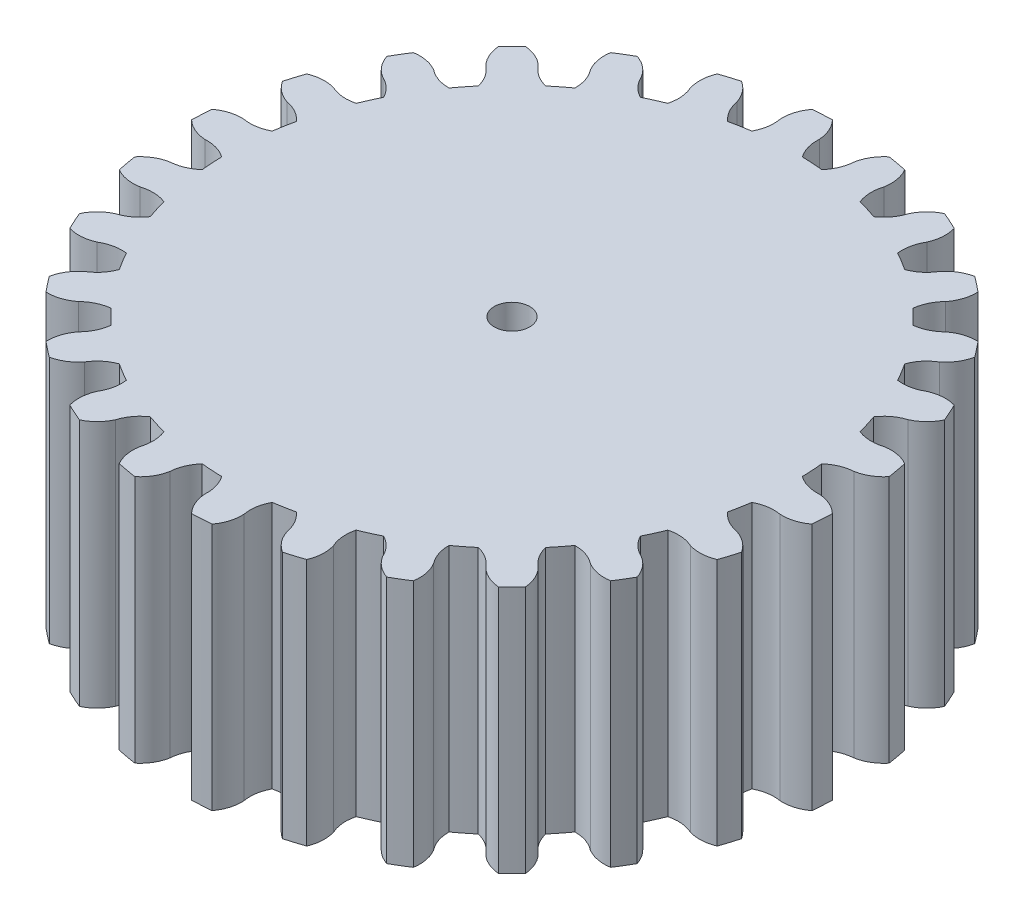
SolidWorks part; units mm, degrees
ref_plane "Alzado" through (0, 0, 0) normal (0, 0, 1) x (1, 0, 0)
ref_plane "Planta" through (0, 0, 0) normal (0, 1, 0) x (1, 0, 0)
ref_plane "Vista lateral" through (0, 0, 0) normal (1, 0, 0) x (0, 0, -1)
sketch "Croquis1" plane through (0, 0, 0) normal (0, 1, 0) x (1, 0, 0)
  circle A0 centre (0, 0) radius 18.6665
  circle A1 centre (0, 0) radius 1
  dimension "D1" = 37.3329
  dimension "D2" = 2
extrude "Saliente-Extruir1" add sketch "Croquis1" along normal blind 14
sketch "Croquis3" plane through (0, 14, 0) normal (0, 1, 0) x (1, 0, 0)
  line L0 (0, 17.333) -> (0, 0) construction
  arc A0 (2.8263, 18.4512) -> (-0.5803, 18.6574) centre (0, 0) ccw
  arc A4 (0, 17.333) -> (0.3822, 15.9949) centre (2.0905, 17.2064) ccw
  arc A5 (2.8263, 18.4512) -> (2.0905, 17.2064) centre (4.1505, 16.8287) ccw
  arc A6 (0, 17.333) -> (-0.5803, 18.6574) centre (-2.0905, 17.2064) ccw
  arc A7 (4.148, 16.8293) -> (3.9016, 18.2541) centre (2.088, 17.2067) ccw
  arc A8 (1.5498, 15.9242) -> (0.3822, 15.9949) centre (0, 0) ccw
  arc A9 (1.5498, 15.9242) -> (2.0905, 17.2064) centre (0, 17.333) ccw
  arc A10 (7.1598, 17.2387) -> (3.9016, 18.2541) centre (0, 0) ccw
  arc A11 (7.1598, 17.2387) -> (6.1475, 16.2061) centre (8.0573, 15.3464) ccw
  arc A12 (5.3156, 15.0906) -> (6.1475, 16.2061) centre (4.148, 16.8293) ccw
  arc A13 (5.3156, 15.0906) -> (4.1989, 15.4386) centre (0, 0) ccw
  arc A14 (4.148, 16.8293) -> (4.1989, 15.4386) centre (6.1475, 16.2061) ccw
  arc A15 (8.055, 15.3476) -> (8.1567, 16.79) centre (6.1452, 16.207) ccw
  arc A16 (11.0773, 15.0243) -> (8.1567, 16.79) centre (0, 0) ccw
  arc A17 (11.0773, 15.0243) -> (9.8473, 14.264) centre (11.4958, 12.9722) ccw
  arc A18 (8.7726, 13.38) -> (9.8473, 14.264) centre (8.055, 15.3476) ccw
  arc A19 (8.7726, 13.38) -> (7.7716, 13.9852) centre (0, 0) ccw
  arc A20 (8.055, 15.3476) -> (7.7716, 13.9852) centre (9.8473, 14.264) ccw
  arc A21 (11.4939, 12.9739) -> (11.9378, 14.3501) centre (9.8452, 14.2655) ccw
  arc A22 (14.351, 11.9368) -> (11.9378, 14.3501) centre (0, 0) ccw
  arc A23 (14.351, 11.9368) -> (12.9747, 11.4929) centre (14.2662, 9.8441) ccw
  arc A24 (11.7197, 10.8918) -> (12.9747, 11.4929) centre (11.4939, 12.9739) ccw
  arc A25 (11.7197, 10.8918) -> (10.8926, 11.7189) centre (0, 0) ccw
  arc A26 (11.4939, 12.9739) -> (10.8926, 11.7189) centre (12.9747, 11.4929) ccw
  arc A27 (14.2647, 9.8462) -> (15.0251, 11.0762) centre (12.9731, 11.4948) ccw
  arc A28 (16.7906, 8.1555) -> (15.0251, 11.0762) centre (0, 0) ccw
  arc A29 (16.7906, 8.1555) -> (15.3482, 8.0539) centre (16.2075, 6.144) ccw
  arc A30 (13.9857, 7.7706) -> (15.3482, 8.0539) centre (14.2647, 9.8462) ccw
  arc A31 (13.9857, 7.7706) -> (13.3806, 8.7716) centre (0, 0) ccw
  arc A32 (14.2647, 9.8462) -> (13.3806, 8.7716) centre (15.3482, 8.0539) ccw
  arc A33 (16.2066, 6.1463) -> (17.2392, 7.1586) centre (15.347, 8.0562) ccw
  arc A34 (18.2544, 3.9003) -> (17.2392, 7.1586) centre (0, 0) ccw
  arc A35 (18.2544, 3.9003) -> (16.8296, 4.1468) centre (17.2069, 2.0867) ccw
  arc A36 (15.439, 4.1978) -> (16.8296, 4.1468) centre (16.2066, 6.1463) ccw
  arc A37 (15.439, 4.1978) -> (15.091, 5.3145) centre (0, 0) ccw
  arc A38 (16.2066, 6.1463) -> (15.091, 5.3145) centre (16.8296, 4.1468) ccw
  arc A39 (17.2066, 2.0893) -> (18.4515, 2.8249) centre (16.829, 4.1493) ccw
  arc A40 (18.6574, -0.5816) -> (18.4515, 2.8249) centre (0, 0) ccw
  arc A41 (18.6574, -0.5816) -> (17.3329, -0.0013) centre (17.2063, -2.0918) ccw
  arc A42 (15.9949, 0.381) -> (17.3329, -0.0013) centre (17.2066, 2.0893) ccw
  arc A43 (15.9949, 0.381) -> (15.9243, 1.5486) centre (0, 0) ccw
  arc A44 (17.2066, 2.0893) -> (15.9243, 1.5486) centre (17.3329, -0.0013) ccw
  arc A45 (17.2066, -2.0893) -> (18.5913, -1.6729) centre (17.3329, 0.0013) ccw
  arc A46 (17.976, -5.0297) -> (18.5913, -1.6729) centre (0, 0) ccw
  arc A47 (17.976, -5.0297) -> (16.829, -4.1493) centre (16.2057, -6.1487) ccw
  arc A48 (15.6213, -3.4579) -> (16.829, -4.1493) centre (17.2066, -2.0893) ccw
  arc A49 (15.6213, -3.4579) -> (15.8322, -2.3074) centre (0, 0) ccw
  arc A50 (17.2066, -2.0893) -> (15.8322, -2.3074) centre (16.829, -4.1493) ccw
  arc A51 (16.2066, -6.1463) -> (17.6508, -6.0735) centre (16.8296, -4.1468) ccw
  arc A52 (16.25, -9.1855) -> (17.6508, -6.0735) centre (0, 0) ccw
  arc A53 (16.25, -9.1855) -> (15.347, -8.0562) centre (14.2633, -9.8483) ccw
  arc A54 (14.3398, -7.0959) -> (15.347, -8.0562) centre (16.2066, -6.1463) ccw
  arc A55 (14.3398, -7.0959) -> (14.82, -6.0292) centre (0, 0) ccw
  arc A56 (16.2066, -6.1463) -> (14.82, -6.0292) centre (15.347, -8.0562) ccw
  arc A57 (14.2647, -9.8462) -> (15.6844, -10.1211) centre (15.3482, -8.0539) ccw
  arc A58 (13.5796, -12.8075) -> (15.6844, -10.1211) centre (0, 0) ccw
  arc A59 (13.5796, -12.8075) -> (12.9731, -11.4948) centre (11.492, -12.9756) ccw
  arc A60 (12.225, -10.3214) -> (12.9731, -11.4948) centre (14.2647, -9.8462) ccw
  arc A61 (12.225, -10.3214) -> (12.9464, -9.4006) centre (0, 0) ccw
  arc A62 (14.2647, -9.8462) -> (12.9464, -9.4006) centre (12.9731, -11.4948) ccw
  arc A63 (11.4939, -12.9739) -> (12.8065, -13.5805) centre (12.9747, -11.4929) ccw
  arc A64 (10.1199, -15.6851) -> (12.8065, -13.5805) centre (0, 0) ccw
  arc A65 (10.1199, -15.6851) -> (9.8452, -14.2655) centre (8.0528, -15.3488) ccw
  arc A66 (9.3997, -12.9471) -> (9.8452, -14.2655) centre (11.4939, -12.9739) ccw
  arc A67 (9.3997, -12.9471) -> (10.3205, -12.2258) centre (0, 0) ccw
  arc A68 (11.4939, -12.9739) -> (10.3205, -12.2258) centre (9.8452, -14.2655) ccw
  arc A69 (8.055, -15.3476) -> (9.1843, -16.2507) centre (9.8473, -14.264) ccw
  arc A70 (6.0722, -17.6512) -> (9.1843, -16.2507) centre (0, 0) ccw
  arc A71 (6.0722, -17.6512) -> (6.1452, -16.207) centre (4.1456, -16.8299) ccw
  arc A72 (6.0281, -14.8204) -> (6.1452, -16.207) centre (8.055, -15.3476) ccw
  arc A73 (6.0281, -14.8204) -> (7.0948, -14.3404) centre (0, 0) ccw
  arc A74 (8.055, -15.3476) -> (7.0948, -14.3404) centre (6.1452, -16.207) ccw
  arc A75 (4.148, -16.8293) -> (5.0284, -17.9764) centre (6.1475, -16.2061) ccw
  arc A76 (1.6715, -18.5915) -> (5.0284, -17.9764) centre (0, 0) ccw
  arc A77 (1.6715, -18.5915) -> (2.088, -17.2067) centre (-0.0026, -17.3329) ccw
  arc A78 (2.3062, -15.8324) -> (2.088, -17.2067) centre (4.148, -16.8293) ccw
  arc A79 (2.3062, -15.8324) -> (3.4568, -15.6216) centre (0, 0) ccw
  arc A80 (4.148, -16.8293) -> (3.4568, -15.6216) centre (2.088, -17.2067) ccw
  arc A81 (0, -17.333) -> (0.5803, -18.6574) centre (2.0905, -17.2064) ccw
  arc A82 (-2.8263, -18.4512) -> (0.5803, -18.6574) centre (0, 0) ccw
  arc A83 (-2.8263, -18.4512) -> (-2.0905, -17.2064) centre (-4.1505, -16.8287) ccw
  arc A84 (-1.5498, -15.9242) -> (-2.0905, -17.2064) centre (0, -17.333) ccw
  arc A85 (-1.5498, -15.9242) -> (-0.3822, -15.9949) centre (0, 0) ccw
  arc A86 (0, -17.333) -> (-0.3822, -15.9949) centre (-2.0905, -17.2064) ccw
  arc A87 (-4.148, -16.8293) -> (-3.9016, -18.2541) centre (-2.088, -17.2067) ccw
  arc A88 (-7.1598, -17.2387) -> (-3.9016, -18.2541) centre (0, 0) ccw
  arc A89 (-7.1598, -17.2387) -> (-6.1475, -16.2061) centre (-8.0573, -15.3464) ccw
  arc A90 (-5.3156, -15.0906) -> (-6.1475, -16.2061) centre (-4.148, -16.8293) ccw
  arc A91 (-5.3156, -15.0906) -> (-4.1989, -15.4386) centre (0, 0) ccw
  arc A92 (-4.148, -16.8293) -> (-4.1989, -15.4386) centre (-6.1475, -16.2061) ccw
  arc A93 (-8.055, -15.3476) -> (-8.1567, -16.79) centre (-6.1452, -16.207) ccw
  arc A94 (-11.0773, -15.0243) -> (-8.1567, -16.79) centre (0, 0) ccw
  arc A95 (-11.0773, -15.0243) -> (-9.8473, -14.264) centre (-11.4958, -12.9722) ccw
  arc A96 (-8.7726, -13.38) -> (-9.8473, -14.264) centre (-8.055, -15.3476) ccw
  arc A97 (-8.7726, -13.38) -> (-7.7716, -13.9852) centre (0, 0) ccw
  arc A98 (-8.055, -15.3476) -> (-7.7716, -13.9852) centre (-9.8473, -14.264) ccw
  arc A99 (-11.4939, -12.9739) -> (-11.9378, -14.3501) centre (-9.8452, -14.2655) ccw
  arc A100 (-14.351, -11.9368) -> (-11.9378, -14.3501) centre (0, 0) ccw
  arc A101 (-14.351, -11.9368) -> (-12.9747, -11.4929) centre (-14.2662, -9.8441) ccw
  arc A102 (-11.7197, -10.8918) -> (-12.9747, -11.4929) centre (-11.4939, -12.9739) ccw
  arc A103 (-11.7197, -10.8918) -> (-10.8926, -11.7189) centre (0, 0) ccw
  arc A104 (-11.4939, -12.9739) -> (-10.8926, -11.7189) centre (-12.9747, -11.4929) ccw
  arc A105 (-14.2647, -9.8462) -> (-15.0251, -11.0762) centre (-12.9731, -11.4948) ccw
  arc A106 (-16.7906, -8.1555) -> (-15.0251, -11.0762) centre (0, 0) ccw
  arc A107 (-16.7906, -8.1555) -> (-15.3482, -8.0539) centre (-16.2075, -6.144) ccw
  arc A108 (-13.9857, -7.7706) -> (-15.3482, -8.0539) centre (-14.2647, -9.8462) ccw
  arc A109 (-13.9857, -7.7706) -> (-13.3806, -8.7716) centre (0, 0) ccw
  arc A110 (-14.2647, -9.8462) -> (-13.3806, -8.7716) centre (-15.3482, -8.0539) ccw
  arc A111 (-16.2066, -6.1463) -> (-17.2392, -7.1586) centre (-15.347, -8.0562) ccw
  arc A112 (-18.2544, -3.9003) -> (-17.2392, -7.1586) centre (0, 0) ccw
  arc A113 (-18.2544, -3.9003) -> (-16.8296, -4.1468) centre (-17.2069, -2.0867) ccw
  arc A114 (-15.439, -4.1978) -> (-16.8296, -4.1468) centre (-16.2066, -6.1463) ccw
  arc A115 (-15.439, -4.1978) -> (-15.091, -5.3145) centre (0, 0) ccw
  arc A116 (-16.2066, -6.1463) -> (-15.091, -5.3145) centre (-16.8296, -4.1468) ccw
  arc A117 (-17.2066, -2.0893) -> (-18.4515, -2.8249) centre (-16.829, -4.1493) ccw
  arc A118 (-18.6574, 0.5816) -> (-18.4515, -2.8249) centre (0, 0) ccw
  arc A119 (-18.6574, 0.5816) -> (-17.3329, 0.0013) centre (-17.2063, 2.0918) ccw
  arc A120 (-15.9949, -0.381) -> (-17.3329, 0.0013) centre (-17.2066, -2.0893) ccw
  arc A121 (-15.9949, -0.381) -> (-15.9243, -1.5486) centre (0, 0) ccw
  arc A122 (-17.2066, -2.0893) -> (-15.9243, -1.5486) centre (-17.3329, 0.0013) ccw
  arc A123 (-17.2066, 2.0893) -> (-18.5913, 1.6729) centre (-17.3329, -0.0013) ccw
  arc A124 (-17.976, 5.0297) -> (-18.5913, 1.6729) centre (0, 0) ccw
  arc A125 (-17.976, 5.0297) -> (-16.829, 4.1493) centre (-16.2057, 6.1487) ccw
  arc A126 (-15.6213, 3.4579) -> (-16.829, 4.1493) centre (-17.2066, 2.0893) ccw
  arc A127 (-15.6213, 3.4579) -> (-15.8322, 2.3074) centre (0, 0) ccw
  arc A128 (-17.2066, 2.0893) -> (-15.8322, 2.3074) centre (-16.829, 4.1493) ccw
  arc A129 (-16.2066, 6.1463) -> (-17.6508, 6.0735) centre (-16.8296, 4.1468) ccw
  arc A130 (-16.25, 9.1855) -> (-17.6508, 6.0735) centre (0, 0) ccw
  arc A131 (-16.25, 9.1855) -> (-15.347, 8.0562) centre (-14.2633, 9.8483) ccw
  arc A132 (-14.3398, 7.0959) -> (-15.347, 8.0562) centre (-16.2066, 6.1463) ccw
  arc A133 (-14.3398, 7.0959) -> (-14.82, 6.0292) centre (0, 0) ccw
  arc A134 (-16.2066, 6.1463) -> (-14.82, 6.0292) centre (-15.347, 8.0562) ccw
  arc A135 (-14.2647, 9.8462) -> (-15.6844, 10.1211) centre (-15.3482, 8.0539) ccw
  arc A136 (-13.5796, 12.8075) -> (-15.6844, 10.1211) centre (0, 0) ccw
  arc A137 (-13.5796, 12.8075) -> (-12.9731, 11.4948) centre (-11.492, 12.9756) ccw
  arc A138 (-12.225, 10.3214) -> (-12.9731, 11.4948) centre (-14.2647, 9.8462) ccw
  arc A139 (-12.225, 10.3214) -> (-12.9464, 9.4006) centre (0, 0) ccw
  arc A140 (-14.2647, 9.8462) -> (-12.9464, 9.4006) centre (-12.9731, 11.4948) ccw
  arc A141 (-11.4939, 12.9739) -> (-12.8065, 13.5805) centre (-12.9747, 11.4929) ccw
  arc A142 (-10.1199, 15.6851) -> (-12.8065, 13.5805) centre (0, 0) ccw
  arc A143 (-10.1199, 15.6851) -> (-9.8452, 14.2655) centre (-8.0528, 15.3488) ccw
  arc A144 (-9.3997, 12.9471) -> (-9.8452, 14.2655) centre (-11.4939, 12.9739) ccw
  arc A145 (-9.3997, 12.9471) -> (-10.3205, 12.2258) centre (0, 0) ccw
  arc A146 (-11.4939, 12.9739) -> (-10.3205, 12.2258) centre (-9.8452, 14.2655) ccw
  arc A147 (-8.055, 15.3476) -> (-9.1843, 16.2507) centre (-9.8473, 14.264) ccw
  arc A148 (-6.0722, 17.6512) -> (-9.1843, 16.2507) centre (0, 0) ccw
  arc A149 (-6.0722, 17.6512) -> (-6.1452, 16.207) centre (-4.1456, 16.8299) ccw
  arc A150 (-6.0281, 14.8204) -> (-6.1452, 16.207) centre (-8.055, 15.3476) ccw
  arc A151 (-6.0281, 14.8204) -> (-7.0948, 14.3404) centre (0, 0) ccw
  arc A152 (-8.055, 15.3476) -> (-7.0948, 14.3404) centre (-6.1452, 16.207) ccw
  arc A153 (-4.148, 16.8293) -> (-5.0284, 17.9764) centre (-6.1475, 16.2061) ccw
  arc A154 (-1.6715, 18.5915) -> (-5.0284, 17.9764) centre (0, 0) ccw
  arc A155 (-1.6715, 18.5915) -> (-2.088, 17.2067) centre (0.0026, 17.3329) ccw
  arc A156 (-2.3062, 15.8324) -> (-2.088, 17.2067) centre (-4.148, 16.8293) ccw
  arc A157 (-2.3062, 15.8324) -> (-3.4568, 15.6216) centre (0, 0) ccw
  arc A158 (-4.148, 16.8293) -> (-3.4568, 15.6216) centre (-2.088, 17.2067) ccw
  point P213 (0, 0)
  dimension "D1" = 37.3329
  dimension "D2" = 26
  dimension "D4" = 4.1887
extrude "Cortar-Extruir2" cut sketch "Croquis3" against normal through all
